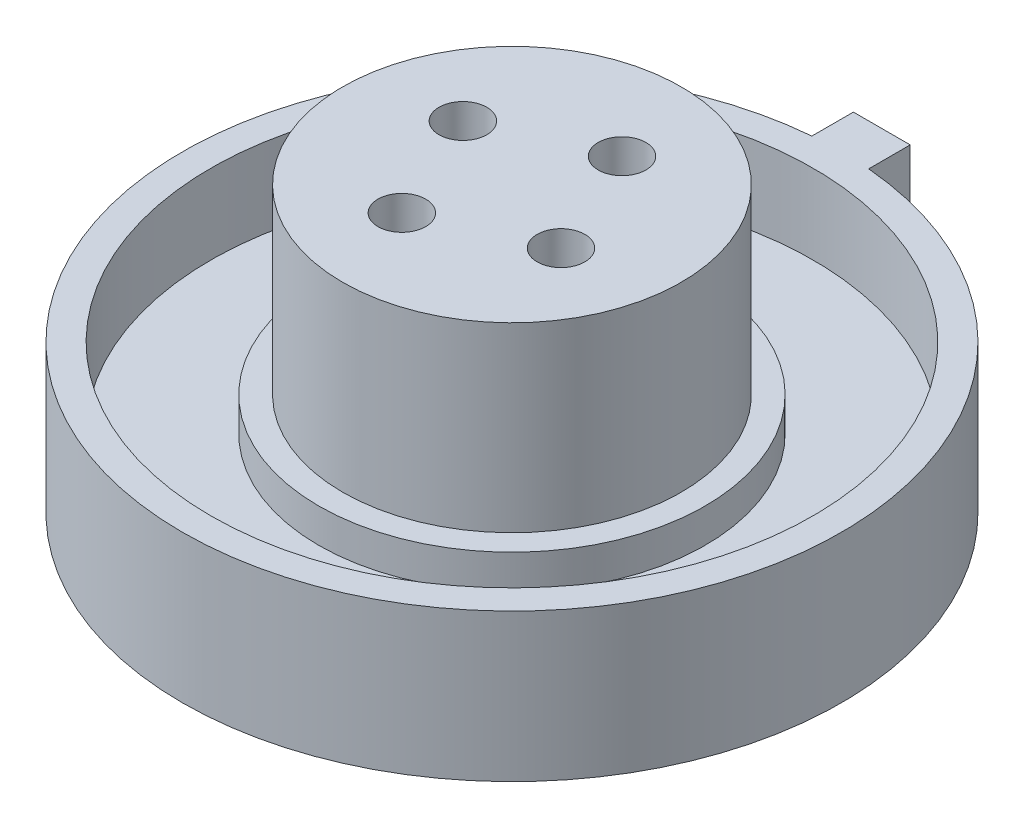
SolidWorks part; units mm, degrees
ref_plane "Front Plane" through (0, 0, 0) normal (0, 0, 1) x (1, 0, 0)
ref_plane "Top Plane" through (0, 0, 0) normal (0, 1, 0) x (1, 0, 0)
ref_plane "Right Plane" through (0, 0, 0) normal (1, 0, 0) x (0, 0, -1)
sketch "Sketch1" plane through (0, 0, 0) normal (0, 1, 0) x (1, 0, 0)
  circle A0 centre (0, 0) radius 29
  dimension "D1" = 58
extrude "Boss-Extrude1" add sketch "Sketch1" along normal blind 13
sketch "Sketch2" plane through (0, 13, 0) normal (0, 1, 0) x (1, 0, 0)
  circle A0 centre (0, 0) radius 26.5
  circle A1 centre (0, 0) radius 17
  dimension "D1" = 53
  dimension "D2" = 34
extrude "Cut-Extrude1" cut sketch "Sketch2" against normal blind 7
sketch "Sketch4" plane through (0, 13, 0) normal (0, 1, 0) x (1, 0, 0)
  circle A0 centre (0, 0) radius 17.25
extrude "Cut-Extrude3" cut sketch "Sketch4" against normal blind 4
sketch "Sketch5" plane through (0, 0, 0) normal (0, -1, 0) x (1, 0, 0)
  line L1 (-2.5, -27.9217) -> (2.5, -27.9217)
  line L2 (-2.5, -27.9217) -> (-2.5, -32.5465)
  line L3 (-2.5, -32.5465) -> (2.5, -32.5465)
  line L4 (2.5, -27.9217) -> (2.5, -32.5465)
  line L5 (-2.5, -27.9217) -> (2.5, -32.5465) construction
  line L6 (-2.5, -32.5465) -> (2.5, -27.9217) construction
  point P0 (0, -30.2341)
  dimension "D1" = 5
extrude "Boss-Extrude2" add sketch "Sketch5" against normal blind 13
sketch "Sketch6" plane through (0, 9, 0) normal (0, 1, 0) x (1, 0, 0)
  circle A0 centre (0, 0) radius 14.9
  dimension "D1" = 29.8
extrude "Boss-Extrude3" add sketch "Sketch6" along normal blind 16
sketch "Sketch3" plane through (0, 0, 0) normal (0, -1, 0) x (1, 0, 0)
  line L0 (7.0026, 2.6857) -> (-7.0026, -2.6857) construction
  line L1 (-2.6857, 7.0026) -> (2.6857, -7.0026) construction
  circle A0 centre (7.0026, 2.6857) radius 2.1
  circle A1 centre (-7.0026, -2.6857) radius 2.1
  circle A2 centre (2.6857, -7.0026) radius 2.1
  circle A3 centre (-2.6857, 7.0026) radius 2.1
  point P4 (0, 0)
  point P9 (0, 0)
  dimension "D2" = 4.2
  dimension "D3" = 4.2
  dimension "D6" = 4.2
  dimension "D7" = 4.2
  dimension "D1" = 15
  dimension "D4" = 90
  dimension "D5" = 15
extrude "Cut-Extrude2" cut sketch "Sketch3" against normal blind 30
